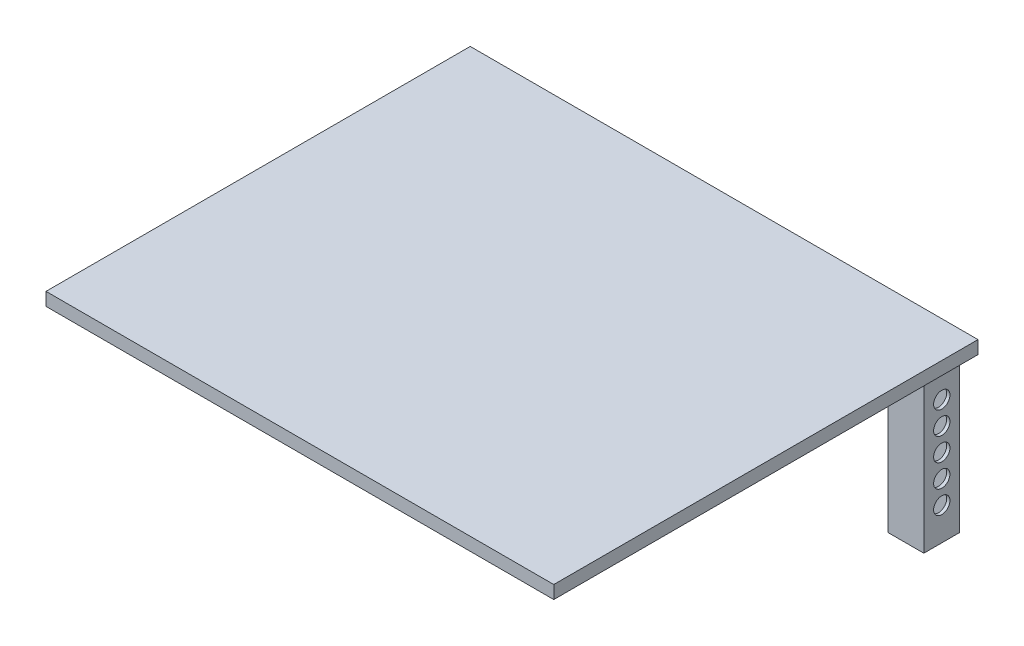
SolidWorks part; units mm, degrees
material "Cast Alloy Steel"
ref_plane "Front Plane" through (0, 0, 0) normal (0, 0, 1) x (1, 0, 0)
ref_plane "Top Plane" through (0, 0, 0) normal (0, 1, 0) x (1, 0, 0)
ref_plane "Right Plane" through (0, 0, 0) normal (1, 0, 0) x (0, 0, -1)
sketch "Sketch1" plane through (0, 0, 0) normal (0, 1, 0) x (1, 0, 0)
  line L1 (-13.97, 13.97) -> (13.97, 13.97)
  line L2 (-13.97, 13.97) -> (-13.97, -13.97)
  line L3 (-13.97, -13.97) -> (13.97, -13.97)
  line L4 (13.97, 13.97) -> (13.97, -13.97)
  line L5 (-13.97, 13.97) -> (13.97, -13.97) construction
  line L6 (-13.97, -13.97) -> (13.97, 13.97) construction
  point P0 (0, 0)
  dimension "D1" = 27.94
  dimension "D2" = 27.94
extrude "Boss-Extrude1" add sketch "Sketch1" along normal blind 127
sketch "Sketch2" plane through (0, 127, 0) normal (0, 1, 0) x (1, 0, 0)
  line L8 (11.43, -11.43) -> (11.43, 11.43)
  line L9 (11.43, 11.43) -> (-11.43, 11.43)
  line L10 (-11.43, 11.43) -> (-11.43, -11.43)
  line L11 (-11.43, -11.43) -> (11.43, -11.43)
  line L12 (11.43, -11.43) -> (11.43, 11.43)
  line L13 (11.43, 11.43) -> (-11.43, 11.43)
  line L14 (-11.43, 11.43) -> (-11.43, -11.43)
  line L15 (-11.43, -11.43) -> (11.43, -11.43)
  dimension "D1" = 2.54
extrude "Cut-Extrude1" cut sketch "Sketch2" against normal up to next
sketch "Sketch3" plane through (0, 127, 0) normal (0, 1, 0) x (1, 0, 0)
  line L1 (13.97, 13.97) -> (-367.03, 13.97)
  line L2 (13.97, 13.97) -> (13.97, -316.23)
  line L3 (13.97, -316.23) -> (-367.03, -316.23)
  line L4 (-367.03, 13.97) -> (-367.03, -316.23)
  dimension "D1" = 330.2
  dimension "D2" = 381
extrude "Boss-Extrude2" add sketch "Sketch3" along normal blind 10.16
sketch "Sketch4" plane through (13.97, 0, 0) normal (1, 0, 0) x (0, 0, -1)
  line L0 (-13.97, 0) -> (13.97, 0) construction
  line L1 (13.97, 137.16) -> (13.97, 0) construction
  circle A0 centre (0, 25.4) radius 6.35
  circle A1 centre (0, 43.18) radius 6.35
  circle A2 centre (0, 60.96) radius 6.35
  circle A3 centre (0, 78.74) radius 6.35
  circle A4 centre (0, 96.52) radius 6.35
  dimension "D1" = 12.7
  dimension "D2" = 25.4
  dimension "D3" = 13.97
  dimension "D5" = 43.18
  dimension "D4" = 5
extrude "Cut-Extrude2" cut sketch "Sketch4" against normal up to next
sketch "Sketch5" plane through (13.97, 0, 0) normal (1, 0, 0) x (0, 0, -1)
  line L1 (-316.23, 137.16) -> (13.97, 137.16)
  line L2 (-316.23, 137.16) -> (-316.23, 127)
  line L3 (-316.23, 127) -> (13.97, 127)
  line L4 (13.97, 137.16) -> (13.97, 127)
extrude "Boss-Extrude3" add sketch "Sketch5" along normal blind 203.2
ref_plane "Plane1" through (-240.03, 0, 0) normal (-1, 0, 0) x (0, 0, 1)
sketch "Sketch6" plane through (0, 127, 0) normal (0, -1, 0) x (1, 0, 0)
  line L8 (-367.03, -13.97) -> (-13.97, -13.97)
  line L9 (-13.97, -13.97) -> (-13.97, 13.97)
  line L10 (-13.97, 13.97) -> (13.97, 13.97)
  line L11 (13.97, 13.97) -> (13.97, -13.97)
  line L12 (13.97, -13.97) -> (217.17, -13.97)
  line L13 (217.17, -13.97) -> (217.17, 316.23)
  line L14 (217.17, 316.23) -> (-367.03, 316.23)
  line L15 (-367.03, 316.23) -> (-367.03, -13.97)
  line L16 (-367.03, -13.97) -> (-13.97, -13.97)
  line L17 (-13.97, -13.97) -> (-13.97, 13.97)
  line L18 (-13.97, 13.97) -> (13.97, 13.97)
  line L19 (13.97, 13.97) -> (13.97, -13.97)
  line L20 (13.97, -13.97) -> (217.17, -13.97)
  line L21 (217.17, -13.97) -> (217.17, 316.23)
  line L22 (217.17, 316.23) -> (-367.03, 316.23)
  line L23 (-367.03, 316.23) -> (-367.03, -13.97)
  circle A0 centre (90.17, 43.5017) radius 7.5
  dimension "D1" = 0
sketch "Sketch7" plane through (0, 127, 0) normal (0, -1, 0) x (1, 0, 0)
  circle A0 centre (90.17, 43.5017) radius 7.5
extrude "Cut-Extrude4" cut sketch "Sketch7" against normal blind 5.08
sketch "Sketch8" plane through (217.17, 0, 0) normal (1, 0, 0) x (0, 0, -1)
  line L4 (-316.23, 137.16) -> (-316.23, 127)
  line L5 (-316.23, 127) -> (13.97, 127)
  line L6 (13.97, 127) -> (13.97, 137.16)
  line L7 (13.97, 137.16) -> (-316.23, 137.16)
  line L8 (-316.23, 137.16) -> (-316.23, 127)
  line L9 (-316.23, 127) -> (13.97, 127)
  line L10 (13.97, 127) -> (13.97, 137.16)
  line L11 (13.97, 137.16) -> (-316.23, 137.16)
  dimension "D1" = 0
extrude "Cut-Extrude5" cut sketch "Sketch8" against normal blind 188.976
